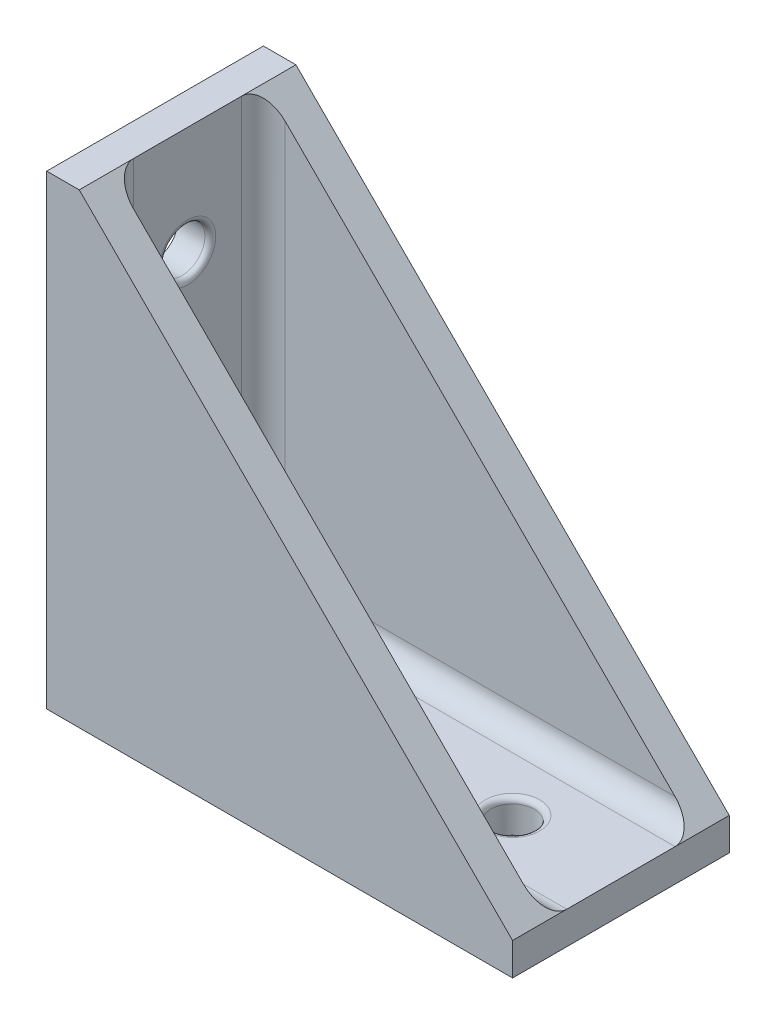
SolidWorks part; units mm, degrees
material "ABS"
ref_plane "Front Plane" through (0, 0, 0) normal (0, 0, 1) x (1, 0, 0)
ref_plane "Top Plane" through (0, 0, 0) normal (0, 1, 0) x (1, 0, 0)
ref_plane "Right Plane" through (0, 0, 0) normal (1, 0, 0) x (0, 0, -1)
sketch "Sketch1" plane through (0, 0, 0) normal (0, 0, 1) x (1, 0, 0)
  line L0 (0, 0) -> (0, 43)
  line L1 (0, 0) -> (43, 0)
  line L2 (0, 43) -> (3, 43)
  line L3 (3, 43) -> (3, 3)
  line L4 (3, 3) -> (43, 3)
  line L5 (43, 3) -> (43, 0)
  dimension "D1" = 3
  dimension "D2" = 3
  dimension "D3" = 40
  dimension "D4" = 40
extrude "Boss-Extrude1" add sketch "Sketch1" along normal blind 20
sketch "Sketch2" plane through (0, 0, 20) normal (0, 0, 1) x (1, 0, 0)
  line L0 (3, 43) -> (43, 3)
  line L1 (43, 3) -> (3, 3)
  line L2 (3, 3) -> (3, 43)
extrude "Boss-Extrude2" add sketch "Sketch2" against normal blind 3
sketch "Sketch3" plane through (0, 0, 0) normal (0, 0, -1) x (-1, 0, 0)
  line L0 (-3, 43) -> (-43, 3)
  line L1 (-43, 3) -> (-3, 3)
  line L2 (-3, 3) -> (-3, 43)
extrude "Boss-Extrude3" add sketch "Sketch3" against normal blind 3
sketch "Sketch4" plane through (3, 0, 0) normal (1, 0, 0) x (0, 0, -1)
  line L0 (-10, 43) -> (-10, 3) construction
  line L1 (-17, 43) -> (-3, 43) construction
  line L2 (-17, 3) -> (-3, 3) construction
  circle A0 centre (-10, 33) radius 2.1
  circle A1 centre (-10, 13) radius 2.1
  point P10 (0, 0)
  dimension "D1" = 4.2
  dimension "D2" = 4.2
  dimension "D3" = 10
  dimension "D4" = 10
extrude "Cut-Extrude1" cut sketch "Sketch4" against normal through all
sketch "Sketch5" plane through (0, 3, 0) normal (0, 1, 0) x (1, 0, 0)
  line L0 (3, -10) -> (43, -10) construction
  line L1 (3, -17) -> (3, -3) construction
  line L2 (43, -17) -> (43, -3) construction
  circle A0 centre (13, -10) radius 2
  circle A1 centre (33, -10) radius 2
  dimension "D1" = 4
  dimension "D2" = 4
  dimension "D3" = 10
  dimension "D4" = 10
extrude "Cut-Extrude2" cut sketch "Sketch5" against normal blind 3
fillet "Fillet3" radius 2 5 edges at (23, 3, 17) (23, 3, 3) (3, 23, 3) (3, 23, 17) (3, 3, 10)
fillet "Fillet4" radius 0.5 4 edges at (3, 15.1, 10) (3, 35.1, 10) (33, 3, 12) (13, 3, 12)
